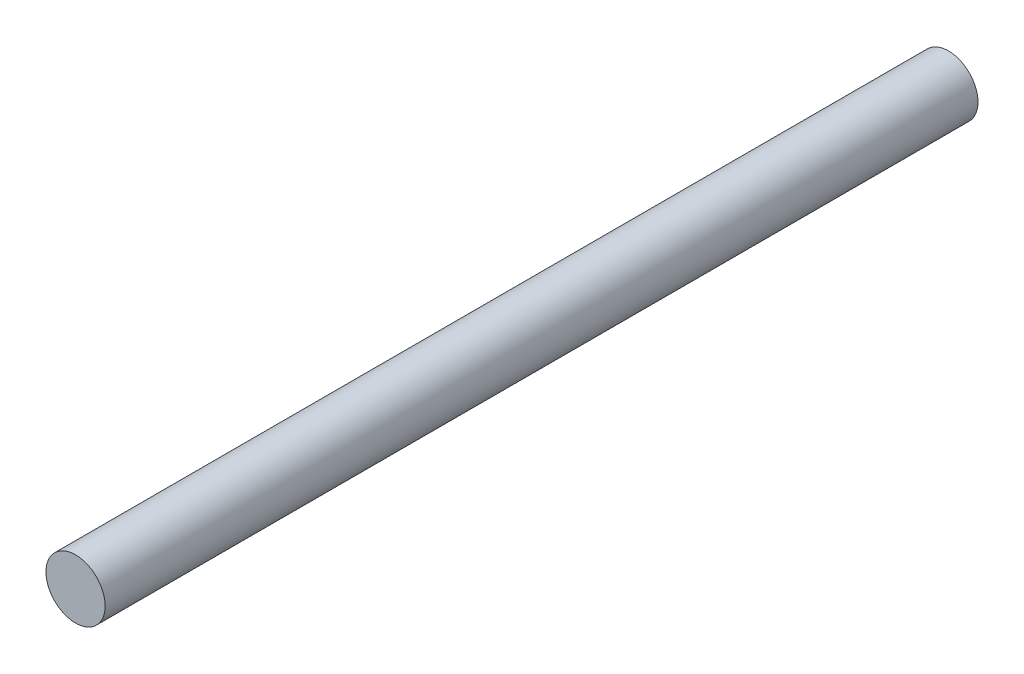
SolidWorks part; units mm, degrees
ref_plane "Front Plane" through (0, 0, 0) normal (0, 0, 1) x (1, 0, 0)
ref_plane "Top Plane" through (0, 0, 0) normal (0, 1, 0) x (1, 0, 0)
ref_plane "Right Plane" through (0, 0, 0) normal (1, 0, 0) x (0, 0, -1)
sketch "Sketch1" plane through (0, 0, 0) normal (0, 0, 1) x (1, 0, 0)
  circle A0 centre (0, 0) radius 3
  dimension "D1" = 6
extrude "Boss-Extrude1" add sketch "Sketch1" along normal blind 88.5
